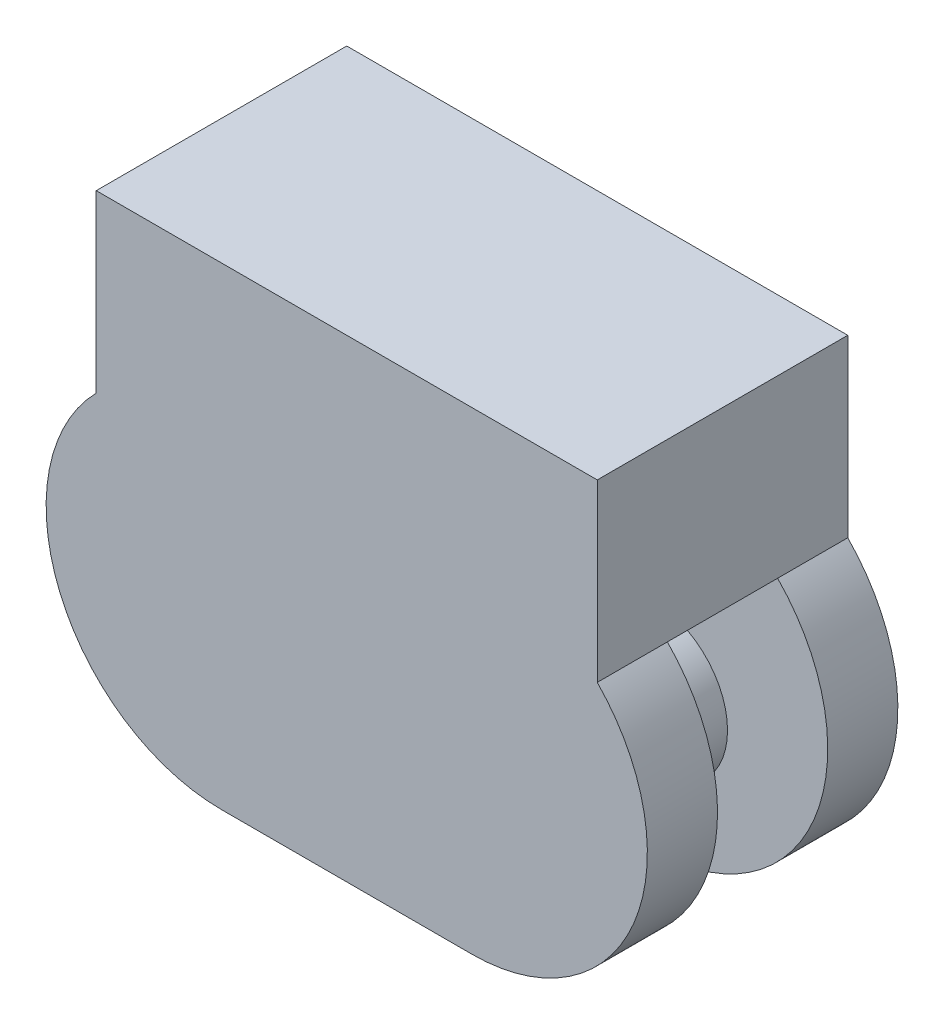
SolidWorks part; units mm, degrees
ref_plane "Front Plane" through (0, 0, 0) normal (0, 0, 1) x (1, 0, 0)
ref_plane "Top Plane" through (0, 0, 0) normal (0, 1, 0) x (1, 0, 0)
ref_plane "Right Plane" through (0, 0, 0) normal (1, 0, 0) x (0, 0, -1)
sketch "Sketch1" plane through (0, 0, 0) normal (0, 0, 1) x (1, 0, 0)
  line L1 (-7.5, 5.9495) -> (2.5, 5.9495)
  line L2 (2.5, 5.9495) -> (2.5, 2.4495)
  line L3 (-7.5, 5.9495) -> (-7.5, 2.4495)
  line L4 (-5, -3.5) -> (0, -3.5)
  arc A1 (2.5, 2.4495) -> (0, -3.5) centre (0, 0) cw
  arc A2 (-7.5, 2.4495) -> (-5, -3.5) centre (-5, 0) ccw
  dimension "D1" = 3.5
  dimension "D3" = 3.5
  dimension "D2" = 10
  dimension "D4" = 3.5
  dimension "D5" = 0
  dimension "D6" = 2.5
  dimension "D7" = 2.5
extrude "Boss-Extrude1" add sketch "Sketch1" along normal blind 5
sketch "Sketch2" plane through (0, 0, 0) normal (1, 0, 0) x (0, 0, -1)
  line L6 (-3.6, 2.4495) -> (-3.6, -3.5)
  line L7 (-1.4, 2.4495) -> (-3.6, 2.4495)
  line L8 (-1.4, 2.4495) -> (-1.4, -3.5)
  line L12 (-3.6, -3.5) -> (-1.4, -3.5)
extrude "Cut-Extrude1" cut sketch "Sketch2" against normal through all both and the other way through all
sketch "Sketch3" plane through (0, 0, 0) normal (0, 0, 1) x (1, 0, 0)
  line L0 (-5, -2.179) -> (0, -2.179)
  line L1 (0, 0.821) -> (-5, 0.821)
  arc A1 (0, 0.821) -> (0, -2.179) centre (0, -0.679) cw
  arc A3 (-5, 0.821) -> (-5, -2.179) centre (-5, -0.679) ccw
  dimension "D1" = 1.5
extrude "Boss-Extrude2" add sketch "Sketch3" along normal blind 5
